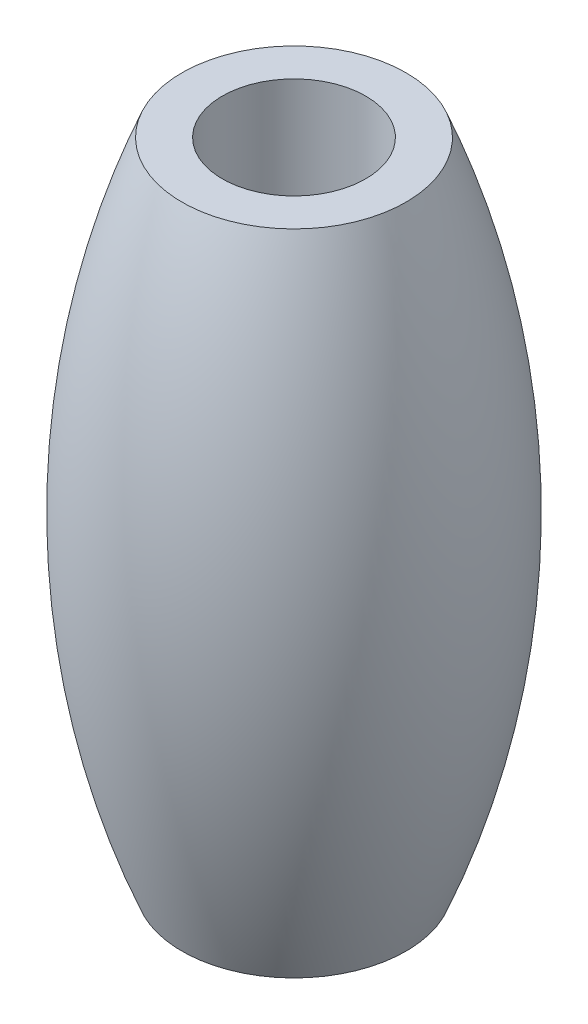
SolidWorks part; units mm, degrees
material "Maple"
ref_plane "Front Plane" through (0, 0, 0) normal (0, 0, 1) x (1, 0, 0)
ref_plane "Top Plane" through (0, 0, 0) normal (0, 1, 0) x (1, 0, 0)
ref_plane "Right Plane" through (0, 0, 0) normal (1, 0, 0) x (0, 0, -1)
sketch "Sketch1" plane through (0, 0, 0) normal (0, 0, 1) x (1, 0, 0)
  line L0 (0, 0) -> (0, 81.6565) construction
  line L1 (7.62, 0) -> (7.62, 68.8962)
  line L2 (7.62, 68.8962) -> (11.9033, 68.8962)
  line L3 (7.62, 0) -> (11.9033, 0)
  arc A0 (11.9033, 68.8962) -> (11.9033, 0) centre (-73.7701, 34.4481) cw
  dimension "D1" = 7.62
revolve "Revolve1" add sketch "Sketch1" angle 360 about L0
